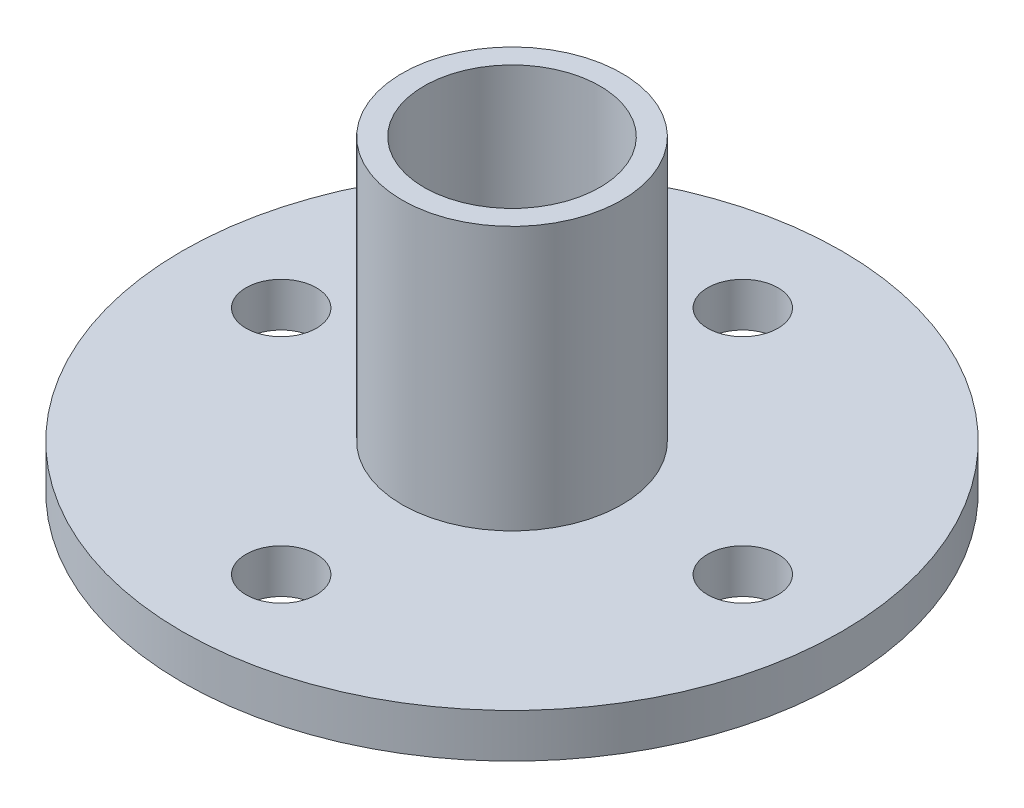
SolidWorks part; units mm, degrees
ref_plane "前视基准面" through (0, 0, 0) normal (0, 0, 1) x (1, 0, 0)
ref_plane "上视基准面" through (0, 0, 0) normal (0, 1, 0) x (1, 0, 0)
ref_plane "右视基准面" through (0, 0, 0) normal (1, 0, 0) x (0, 0, -1)
other "Configuration Table"
sketch "草图1" plane through (0, 0, 0) normal (0, 1, 0) x (1, 0, 0)
  circle A0 centre (0, 0) radius 15
  dimension "D1" = 30
extrude "凸台-拉伸1" add sketch "草图1" along normal blind 2
sketch "草图2" plane through (0, 2, 0) normal (0, 1, 0) x (1, 0, 0)
  circle A0 centre (0, 0) radius 4
  circle A1 centre (0, 0) radius 5
  dimension "D1" = 8
  dimension "D2" = 10
extrude "凸台-拉伸2" add sketch "草图2" along normal blind 12
sketch "草图3" plane through (0, 2, 0) normal (0, 1, 0) x (1, 0, 0)
  circle A0 centre (0, 0) radius 4
extrude "切除-拉伸1" cut sketch "草图3" against normal blind 12
sketch "草图4" plane through (0, 2, 0) normal (0, 1, 0) x (1, 0, 0)
  circle A0 centre (0, 0) radius 10.5 construction
  circle A1 centre (0, 10.5) radius 1.6
  circle A2 centre (10.5, 0) radius 1.6
  circle A3 centre (0, -10.5) radius 1.6
  circle A4 centre (-10.5, 0) radius 1.6
  point P14 (0, 0)
  dimension "D1" = 21
  dimension "D2" = 3.2
  dimension "D3" = 4
extrude "切除-拉伸2" cut sketch "草图4" against normal blind 12
